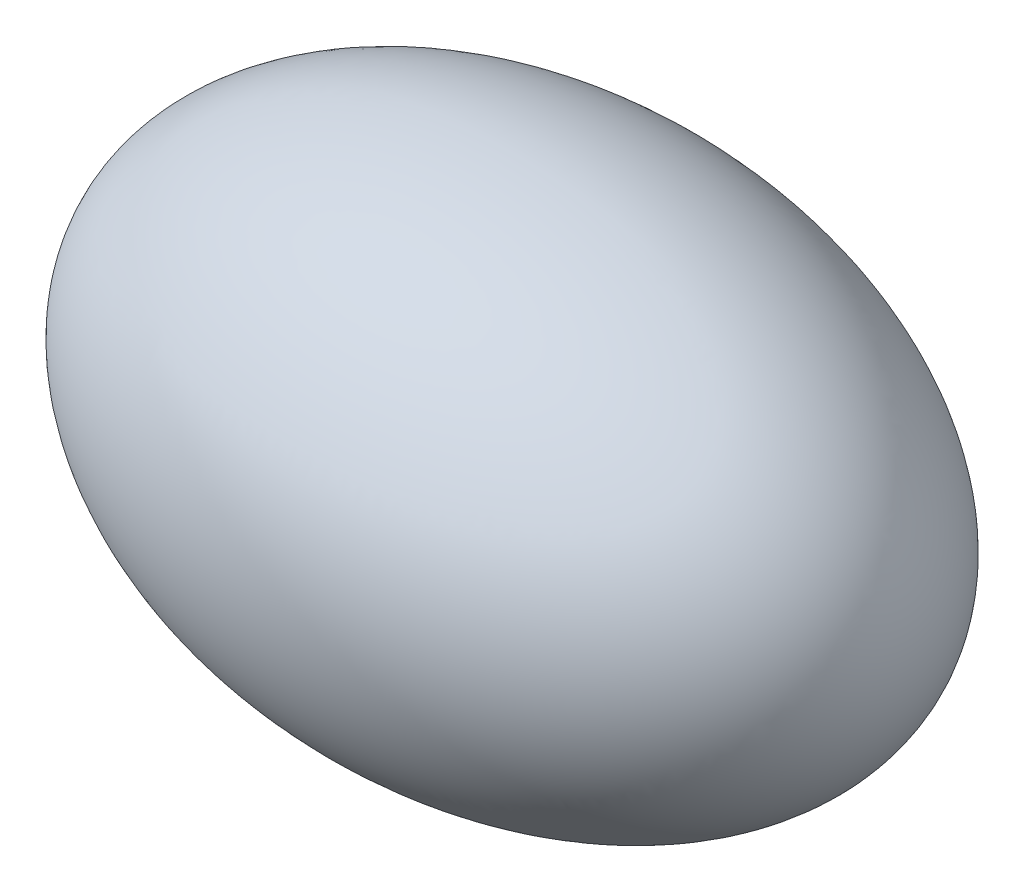
SolidWorks part; units mm, degrees
material "Natural Rubber"
ref_plane "Front Plane" through (0, 0, 0) normal (0, 0, 1) x (1, 0, 0)
ref_plane "Top Plane" through (0, 0, 0) normal (0, 1, 0) x (1, 0, 0)
ref_plane "Right Plane" through (0, 0, 0) normal (1, 0, 0) x (0, 0, -1)
sketch "Sketch1" plane through (0, 0, 0) normal (0, 0, 1) x (1, 0, 0)
  line L0 (-129.54, 0) -> (129.54, 0)
  line L1 (-129.54, 0) -> (129.54, 0) construction
  ellipse E0 centre (0, 0) end of major axis (129.54, 0) minor radius 85.09 (129.54, 0) -> (-129.54, 0) ccw
  point P1 (0, 0)
  point P7 (0, 0)
revolve "Revolve2" add sketch "Sketch1" angle 360 about L1
